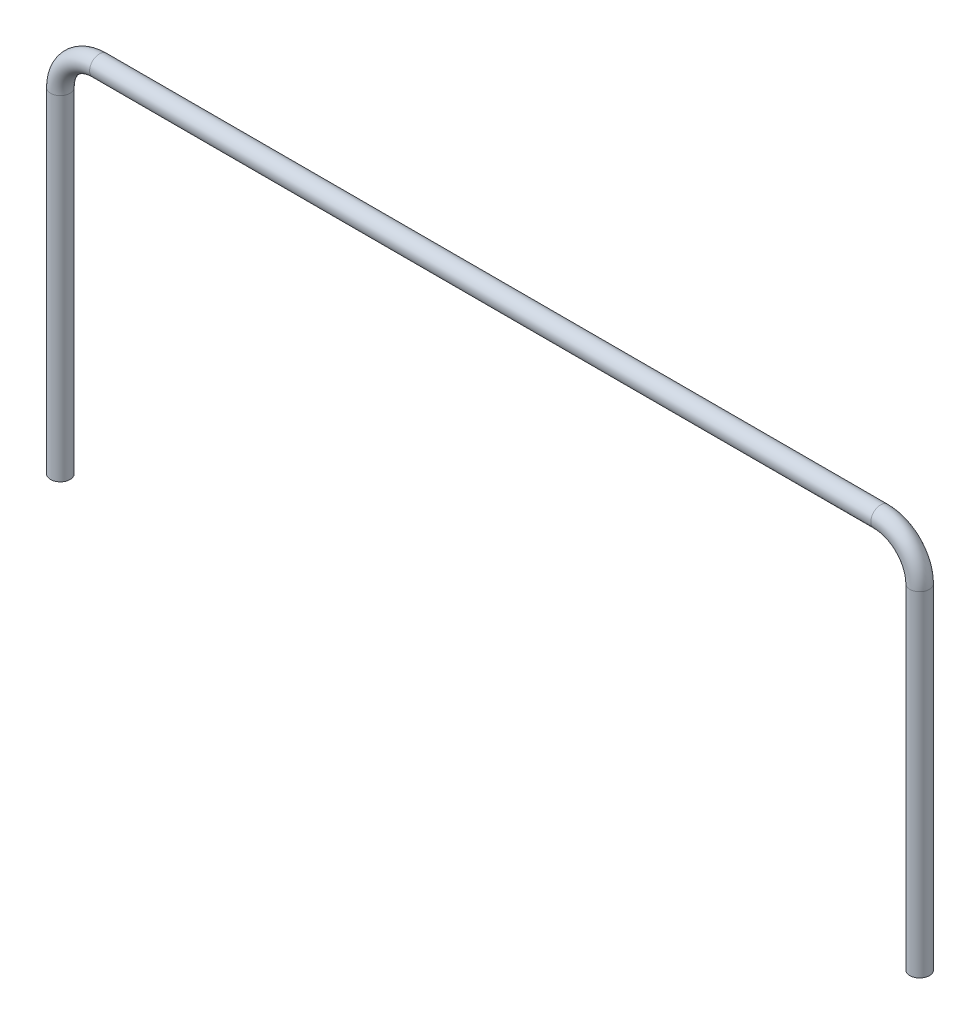
SolidWorks part; units mm, degrees
ref_plane "Plan de face" through (0, 0, 0) normal (0, 0, 1) x (1, 0, 0)
ref_plane "Plan de dessus" through (0, 0, 0) normal (0, 1, 0) x (1, 0, 0)
ref_plane "Plan de droite" through (0, 0, 0) normal (1, 0, 0) x (0, 0, -1)
sketch "Esquisse1" plane through (0, 0, 0) normal (0, 0, 1) x (1, 0, 0)
  line L0 (0, 0) -> (-15.5605, 0) construction
  line L1 (-6.6789, 19.1292) -> (33.3211, 19.1292)
  line L2 (-8.6789, 17.1292) -> (-8.6789, 0)
  line L4 (35.3211, 17.1292) -> (35.3211, 0)
  arc A0 (-6.6789, 19.1292) -> (-8.6789, 17.1292) centre (-6.6789, 17.1292) ccw
  arc A1 (35.3211, 17.1292) -> (33.3211, 19.1292) centre (33.3211, 17.1292) ccw
  dimension "D1" = 2
  dimension "D2" = 2
  dimension "D3" = 44
sketch "Esquisse2" plane through (0, 0, 0) normal (0, 1, 0) x (1, 0, 0)
  circle A0 centre (-8.6789, 0) radius 0.5
  dimension "D1" = 1
sweep "Balayage1" add profiles "Esquisse2" path "Esquisse1"
